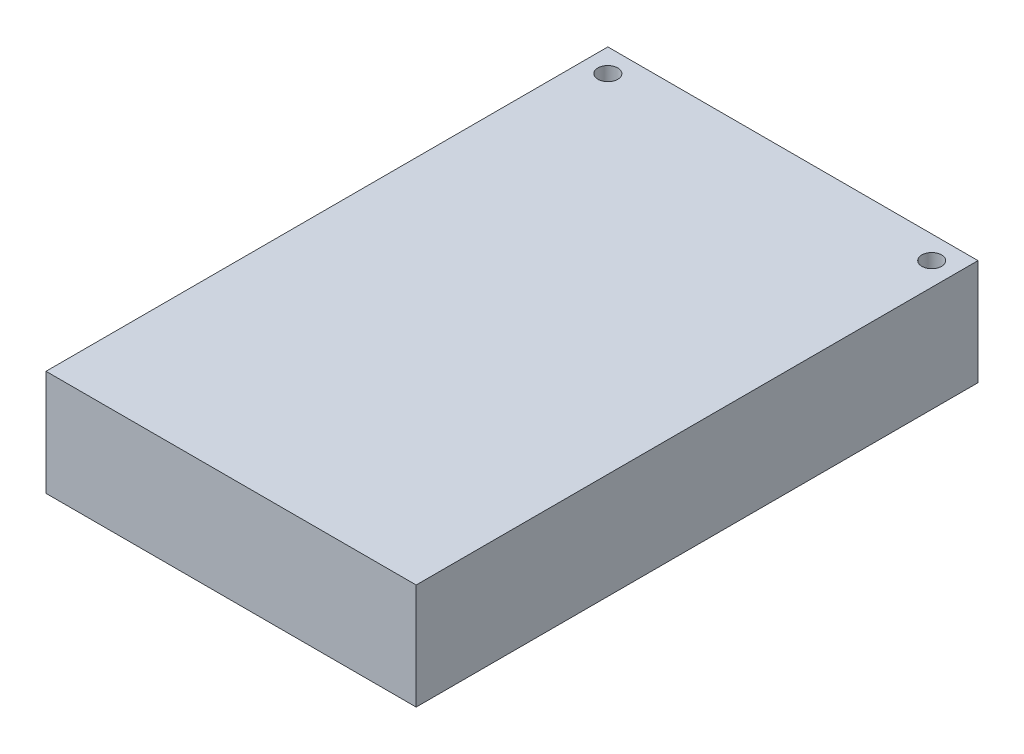
SolidWorks part; units mm, degrees
ref_plane "前视基准面" through (0, 0, 0) normal (0, 0, 1) x (1, 0, 0)
ref_plane "上视基准面" through (0, 0, 0) normal (0, 1, 0) x (1, 0, 0)
ref_plane "右视基准面" through (0, 0, 0) normal (1, 0, 0) x (0, 0, -1)
sketch "草图1" plane through (0, 0, 0) normal (0, 0, 1) x (1, 0, 0)
  line L1 (0, 0) -> (56, 0)
  line L2 (0, 0) -> (0, 16)
  line L3 (0, 16) -> (56, 16)
  line L4 (56, 0) -> (56, 16)
extrude "凸台-拉伸1" add sketch "草图1" along normal blind 85
sketch "草图2" plane through (0, 16, 0) normal (0, 1, 0) x (1, 0, 0)
  circle A2 centre (3.5, -3.5) radius 1.5
  circle A3 centre (52.5, -3.5) radius 1.5
extrude "切除-拉伸1" cut sketch "草图2" against normal through all
